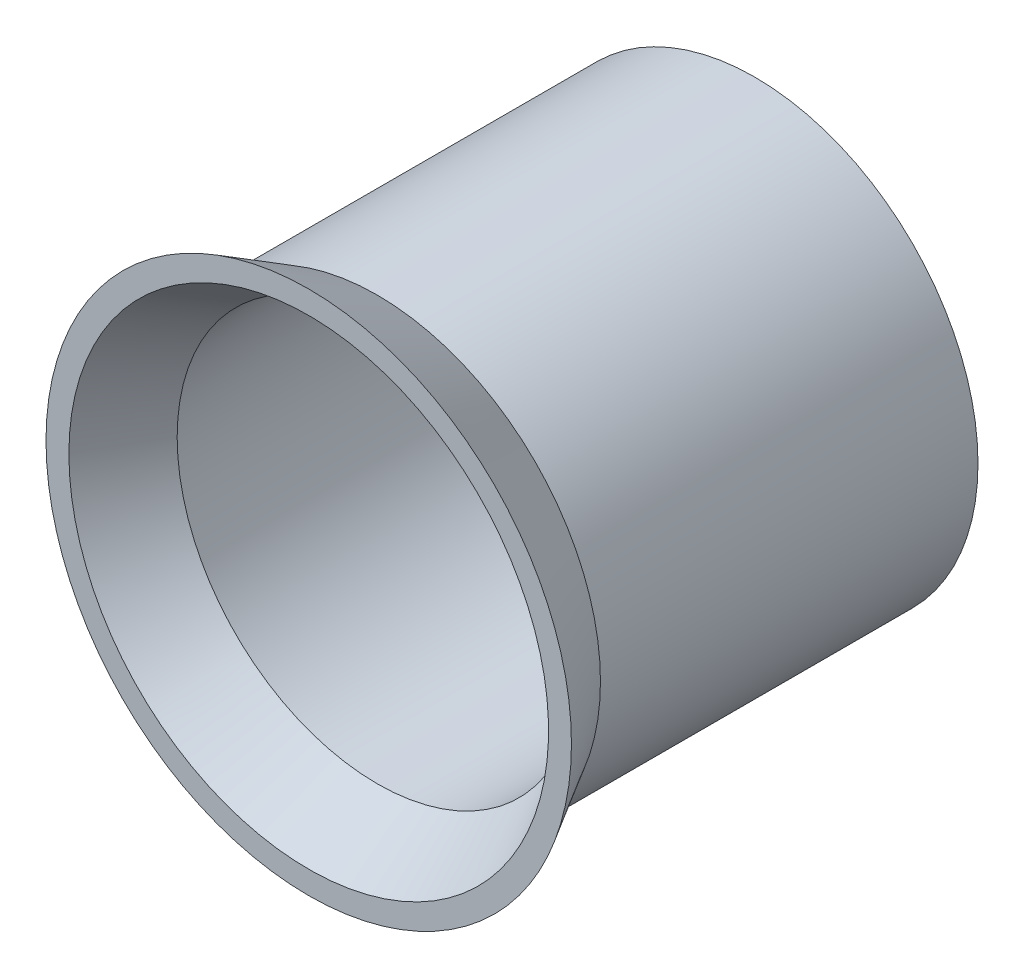
SolidWorks part; units mm, degrees
ref_plane "Front Plane" through (0, 0, 0) normal (0, 0, 1) x (1, 0, 0)
ref_plane "Top Plane" through (0, 0, 0) normal (0, 1, 0) x (1, 0, 0)
ref_plane "Right Plane" through (0, 0, 0) normal (1, 0, 0) x (0, 0, -1)
sketch "Sketch1" plane through (0, 0, 0) normal (0, 0, 1) x (1, 0, 0)
  circle A0 centre (0, 0) radius 19.5
  dimension "D1" = 39
extrude "Boss-Extrude1" add sketch "Sketch1" along normal blind 37
shell "Shell1" thickness 2
sketch "Sketch2" plane through (0, 0, 2) normal (0, 0, 1) x (1, 0, 0)
  circle A0 centre (0, 0) radius 17.5
  circle A1 centre (0, 0) radius 17.1
  dimension "D1" = 34.2
extrude "Boss-Extrude2" add sketch "Sketch2" along normal blind 2
sketch "Sketch3" plane through (0, 0, 37) normal (0, 0, 1) x (1, 0, 0)
  circle A0 centre (0, 0) radius 19.5
extrude "Cut-Extrude1" cut sketch "Sketch3" against normal blind 4
sketch "Sketch4" plane through (0, 0, 0) normal (0, 1, 0) x (1, 0, 0)
  line L0 (19.5, -33) -> (22.9641, -39)
  line L1 (22.9641, -39) -> (20.9641, -39)
  line L2 (20.9641, -39) -> (17.5, -33)
  line L3 (-19.5, -33) -> (19.5, -33) construction
  line L4 (-17.5, -33) -> (17.5, -33) construction
  line L5 (17.5, -33) -> (19.5, -33)
  line L6 (0, -33) -> (0, -43.5814) construction
  dimension "D1" = 2
  dimension "D2" = 6
  dimension "D3" = 2
  dimension "D4" = 60
revolve "Revolve1" add sketch "Sketch4" angle 360 about L6
